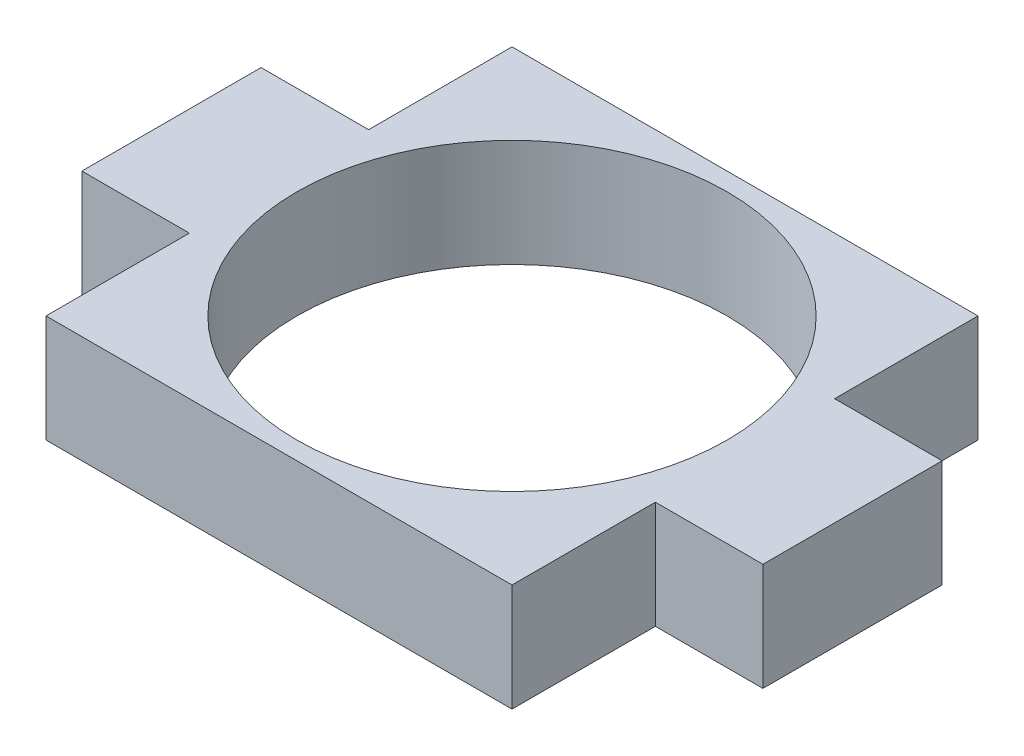
SolidWorks part; units mm, degrees
ref_plane "Plan de face" through (0, 0, 0) normal (0, 0, 1) x (1, 0, 0)
ref_plane "Plan de dessus" through (0, 0, 0) normal (0, 1, 0) x (1, 0, 0)
ref_plane "Plan de droite" through (0, 0, 0) normal (1, 0, 0) x (0, 0, -1)
sketch "Sketch1" plane through (0, 0, 0) normal (0, 1, 0) x (1, 0, 0)
  line L1 (6.5, -6.5) -> (-6.5, -6.5)
  line L2 (6.5, -6.5) -> (6.5, 6.5)
  line L3 (6.5, 6.5) -> (-6.5, 6.5)
  line L4 (-6.5, -6.5) -> (-6.5, 6.5)
  line L5 (6.5, -6.5) -> (-6.5, 6.5) construction
  line L6 (6.5, 6.5) -> (-6.5, -6.5) construction
  point P0 (0, 0)
  dimension "D1" = 13
  dimension "D2" = 13
extrude "Boss-Extrude1" add sketch "Sketch1" along normal blind 3
sketch "Sketch2" plane through (0, 3, 0) normal (0, 1, 0) x (1, 0, 0)
  circle A0 centre (0, 0) radius 6
  dimension "D1" = 12
extrude "Cut-Extrude1" cut sketch "Sketch2" against normal blind 3
sketch "Sketch4" plane through (0, 3, 0) normal (0, 1, 0) x (1, 0, 0)
  line L0 (-6.5, 6.5) -> (-6.5, -6.5) construction
  line L1 (-6.5, 2.5) -> (-9.5, 2.5)
  line L2 (-6.5, 2.5) -> (-6.5, -2.5)
  line L3 (-6.5, -2.5) -> (-9.5, -2.5)
  line L4 (-9.5, 2.5) -> (-9.5, -2.5)
  line L5 (6.5, 6.5) -> (-6.5, 6.5) construction
  line L7 (6.5, -6.5) -> (6.5, 6.5) construction
  line L8 (6.5, 2.5) -> (9.5, 2.5)
  line L9 (6.5, 2.5) -> (6.5, -2.5)
  line L10 (6.5, -2.5) -> (9.5, -2.5)
  line L11 (9.5, 2.5) -> (9.5, -2.5)
  dimension "D1" = 5
  dimension "D2" = 4
  dimension "D3" = 3
  dimension "D4" = 5
  dimension "D5" = 3
extrude "Boss-Extrude2" add sketch "Sketch4" against normal blind 3
